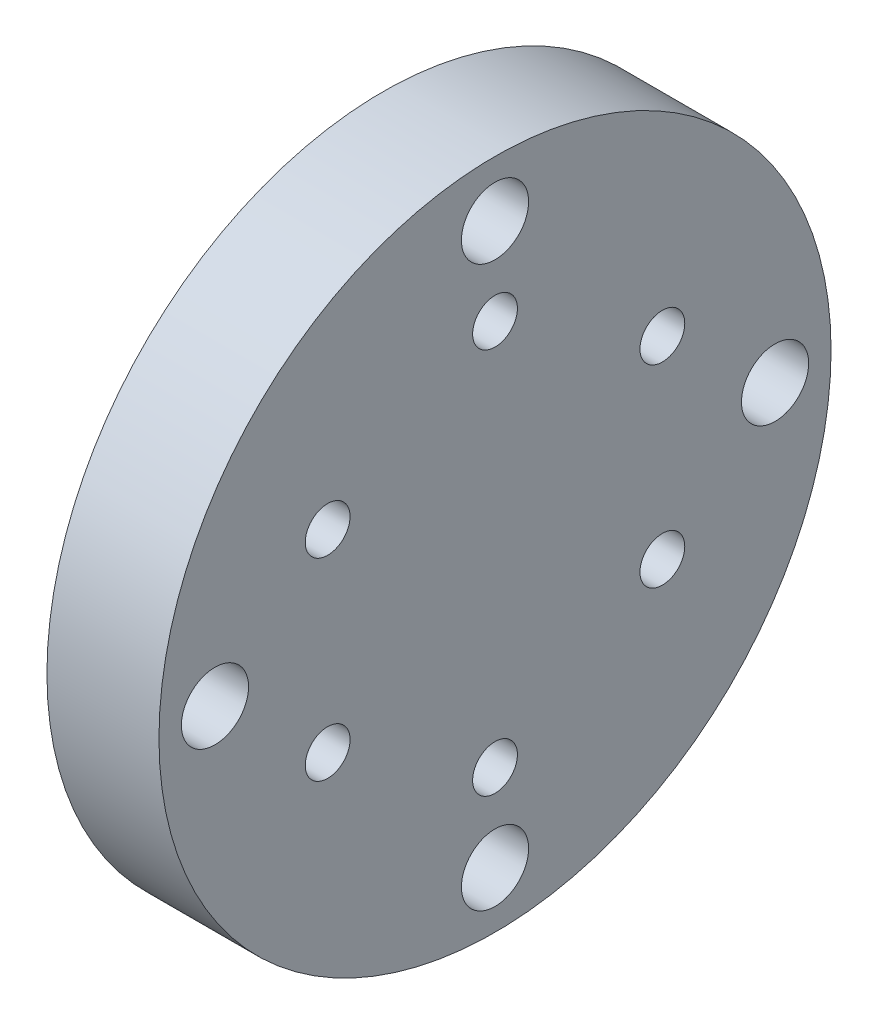
SolidWorks part; units mm, degrees
ref_plane "前视基准面" through (0, 0, 0) normal (0, 0, 1) x (1, 0, 0)
ref_plane "上视基准面" through (0, 0, 0) normal (0, 1, 0) x (1, 0, 0)
ref_plane "右视基准面" through (0, 0, 0) normal (1, 0, 0) x (0, 0, -1)
sketch "草图1" plane through (0, 0, 0) normal (1, 0, 0) x (0, 0, -1)
  circle A0 centre (-12.8484, 0.0481) radius 25
  circle A1 centre (-12.8484, 0.0481) radius 17.25
  circle A2 centre (-12.8484, 17.2981) radius 2
  circle A3 centre (2.0905, 8.6731) radius 2
  circle A4 centre (2.0905, -8.5769) radius 2
  circle A5 centre (-12.8484, -17.2019) radius 2
  circle A6 centre (-27.7873, -8.5769) radius 2
  circle A7 centre (-27.7873, 8.6731) radius 2
  circle A8 centre (-12.8484, 0.0481) radius 30
  circle A9 centre (-12.8484, 25.0481) radius 3
  circle A10 centre (12.1516, 0.0481) radius 3
  circle A11 centre (-12.8484, -24.9519) radius 3
  circle A12 centre (-37.8484, 0.0481) radius 3
  point P18 (-12.8484, 0.0481)
  point P28 (-12.8484, 0.0481)
  dimension "D1" = 34.5
  dimension "D2" = 50
  dimension "D3" = 6
  dimension "D4" = 4
extrude "凸台-拉伸1" add sketch "草图1" along normal blind 10 contours A8 A12 A0 A9 A10 A11 | A12 A0 A11 A10 A9 A7 A1 A2 A3 A4 A5 A6 | A7 A1 A6 A5 A4 A3 A2
